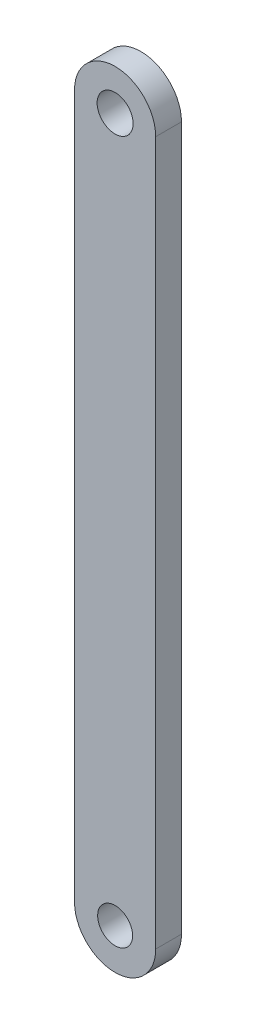
SolidWorks part; units mm, degrees
material "ABS"
ref_plane "Plano frontal" through (0, 0, 0) normal (0, 0, 1) x (1, 0, 0)
ref_plane "Plano superior" through (0, 0, 0) normal (0, 1, 0) x (1, 0, 0)
ref_plane "Plano direito" through (0, 0, 0) normal (1, 0, 0) x (0, 0, -1)
sketch "Esboço1" plane through (0, 0, 0) normal (0, 0, 1) x (1, 0, 0)
  line L0 (0, 0) -> (0, 130) construction
  line L1 (-7.5, 0) -> (-7.5, 130)
  line L2 (7.5, 0) -> (7.5, 130)
  arc A0 (-7.5, 0) -> (7.5, 0) centre (0, 0) ccw
  arc A1 (7.5, 130) -> (-7.5, 130) centre (0, 130) ccw
  circle A5 centre (0, 130) radius 3.325
  circle A6 centre (0, 0) radius 3.225
  point P3 (0, 65)
  dimension "D1" = 6.45
  dimension "D3" = 6.65
  dimension "D4" = 130
  dimension "D5" = 15
extrude "Ressalto-extrusão1" add sketch "Esboço1" along normal blind 4.7625
